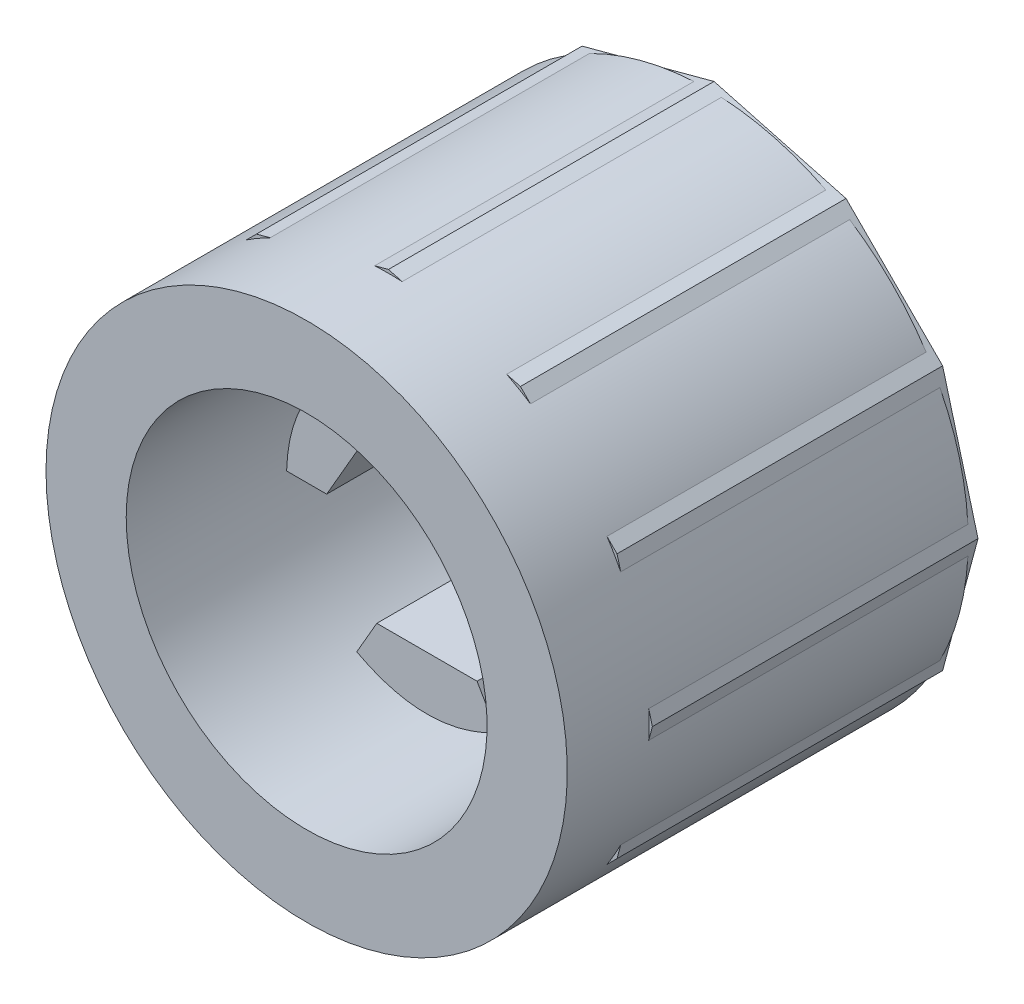
SolidWorks part; units mm, degrees
ref_plane "Front Plane" through (0, 0, 0) normal (0, 0, 1) x (1, 0, 0)
ref_plane "Top Plane" through (0, 0, 0) normal (0, 1, 0) x (1, 0, 0)
ref_plane "Right Plane" through (0, 0, 0) normal (1, 0, 0) x (0, 0, -1)
sketch "Sketch1" plane through (0, 0, 0) normal (0, 1, 0) x (1, 0, 0)
  line L0 (-4.8418, 12.6364) -> (-4.8418, 11.0489)
  line L1 (-4.8418, 12.6364) -> (5.477, 12.6364)
  line L2 (-4.8418, 12.6364) -> (-4.8418, -3.2386)
  line L3 (-4.8418, -3.2386) -> (5.477, -3.2386)
  line L4 (5.477, 12.6364) -> (5.477, -3.2386)
  line L5 (-4.8418, 11.0489) -> (-0.873, 11.0489)
  line L7 (5.477, 12.6364) -> (3.8895, 12.6364)
  line L9 (-0.873, 11.0489) -> (-0.873, 6.2864)
  line L10 (-0.873, 6.2864) -> (0.7145, 6.2864)
  line L11 (0.7145, 11.0489) -> (0.7145, 6.2864)
  line L12 (0.7145, 11.0489) -> (2.302, 11.0489)
  line L13 (2.302, 11.0489) -> (2.302, -3.2386)
  dimension "D1" = 10.3187
  dimension "D2" = 15.875
  dimension "D3" = 1.5875
  dimension "D4" = 3.9688
  dimension "D5" = 1.5875
  dimension "D6" = 3.175
  dimension "D7" = 1.5875
revolve "Revolve1" add sketch "Sketch1" angle 360 about L2
sketch "Sketch3" plane through (0, 0, -11.0489) normal (0, 0, 1) x (1, 0, 0)
  line L1 (-0.873, 0) -> (-2.8574, 3.437)
  line L2 (-2.8574, 3.437) -> (-6.8262, 3.437)
  line L3 (-6.8262, 3.437) -> (-8.8105, 0)
  line L4 (-8.8105, 0) -> (-6.8262, -3.437)
  line L5 (-6.8262, -3.437) -> (-2.8574, -3.437)
  line L6 (-2.8574, -3.437) -> (-0.873, 0)
  circle A0 centre (-4.8418, 0) radius 3.437 construction
extrude "Extrude-Thin1" add sketch "Sketch3" along normal blind 4.7625 thin
sketch "Sketch4" plane through (0, 0, -6.2864) normal (0, 0, 1) x (1, 0, 0)
  line L0 (-8.8105, 0) -> (-10.398, 0)
  line L1 (-6.8262, 3.437) -> (-7.6199, 4.8119)
  line L2 (-6.8262, 3.437) -> (-8.8105, 0) construction
  line L3 (-6.8262, 3.437) -> (-8.8105, 0) construction
  line L4 (-6.8262, 3.437) -> (-8.8105, 0)
  circle A0 centre (-4.8418, 0) radius 5.5563 construction
  circle A1 centre (-4.8418, 0) radius 5.5563 construction
  spline S0 degree 2 poles (-7.6199, 4.8119) (-10.3011, 3.1454) (-10.398, 0) knots 0 0 0 1 1 1
extrude "Boss-Extrude3" add sketch "Sketch4" along normal blind 4.7625 contours L1 S0 L0 L4
sketch "Sketch6" plane through (0, 0, -6.2864) normal (0, 0, 1) x (1, 0, 0)
  line L0 (-2.8574, 3.437) -> (-2.0637, 4.8119)
  line L2 (-0.873, 0) -> (0.7145, 0)
  line L3 (-2.8574, 3.437) -> (-0.873, 0)
  circle A0 centre (-4.8418, 0) radius 5.5563 construction
  arc A1 (-10.398, 0) -> (-7.6199, 4.8119) centre (-4.8418, 0) ccw construction
  spline S0 degree 2 poles (-2.0637, 4.8119) (0.6187, 3.1433) (0.7145, 0) knots 0 0 0 1 1 1
extrude "Boss-Extrude4" add sketch "Sketch6" along normal blind 4.7625
sketch "Sketch7" plane through (0, 0, -6.2864) normal (0, 0, 1) x (1, 0, 0)
  line L0 (-6.8262, -3.437) -> (-7.6199, -4.8119)
  line L1 (-2.8574, -3.437) -> (-2.0637, -4.8119)
  line L2 (-6.8262, -3.437) -> (-2.8574, -3.437)
  circle A0 centre (-4.8418, 0) radius 5.5563 construction
  arc A1 (-10.398, 0) -> (0.7145, 0) centre (-4.8418, 0) ccw construction
  spline S0 degree 2 poles (-7.6199, -4.8119) (-4.8418, -6.3006) (-2.0637, -4.8119) knots 0 0 0 1 1 1
extrude "Boss-Extrude5" add sketch "Sketch7" along normal blind 4.7625 contours L0 S0 L1 L2
sketch "Sketch11" plane through (0, 0, 0) normal (0, 0, 1) x (1, 0, 0)
  line L1 (-15.1605, 0) -> (-13.7781, -5.1594)
  line L2 (-13.7781, -5.1594) -> (-10.0012, -8.9363)
  line L3 (-10.0012, -8.9363) -> (-4.8418, -10.3187)
  line L4 (-4.8418, -10.3187) -> (0.3176, -8.9363)
  line L5 (0.3176, -8.9363) -> (4.0945, -5.1594)
  line L6 (4.0945, -5.1594) -> (5.477, 0)
  line L7 (5.477, 0) -> (4.0945, 5.1594)
  line L8 (4.0945, 5.1594) -> (0.3176, 8.9363)
  line L9 (0.3176, 8.9363) -> (-4.8418, 10.3187)
  line L10 (-4.8418, 10.3187) -> (-10.0012, 8.9363)
  line L11 (-10.0012, 8.9363) -> (-13.7781, 5.1594)
  line L12 (-13.7781, 5.1594) -> (-15.1605, 0)
  circle A0 centre (-4.8418, 0) radius 9.9671 construction
  point P1 (-4.8418, 0)
extrude "Extrude-Thin2" add sketch "Sketch11" along a picked direction on the side against the normal blind 12.8905 thin thin type mid plane wall 0.254
